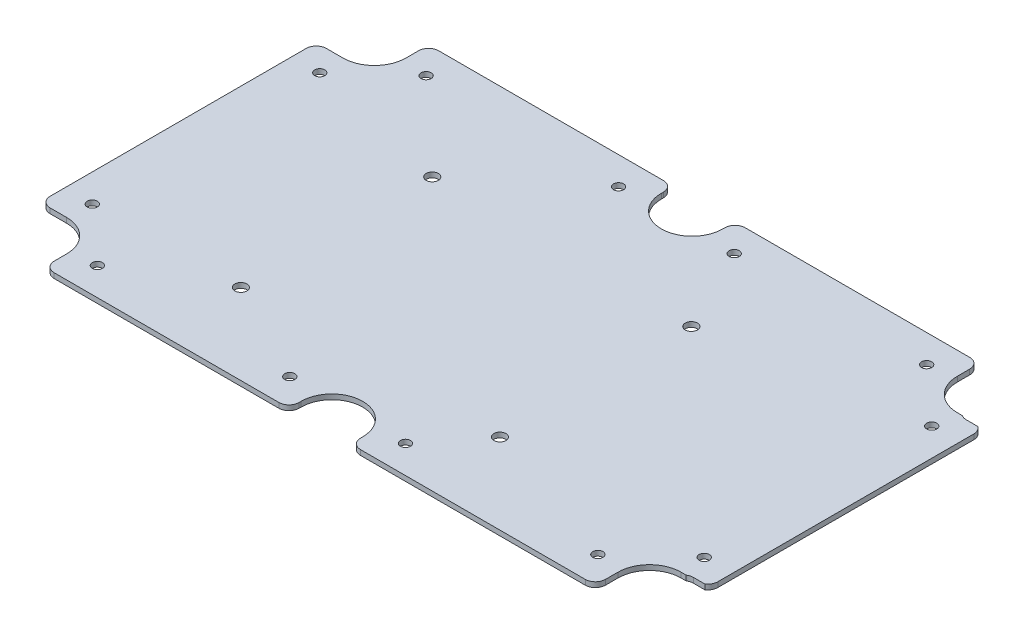
SolidWorks part; units mm, degrees
ref_plane "Front Plane" through (0, 0, 0) normal (0, 0, 1) x (1, 0, 0)
ref_plane "Top Plane" through (0, 0, 0) normal (0, 1, 0) x (1, 0, 0)
ref_plane "Right Plane" through (0, 0, 0) normal (1, 0, 0) x (0, 0, -1)
ref_plane "Plane1" through (0, 9.652, 0) normal (0, -1, 0) x (1, 0, 0)
sketch "Sketch1" plane through (0, 9.652, 0) normal (0, -1, 0) x (1, 0, 0)
  line L0 (-9.6495, -57.089) -> (-9.6495, -56.4515)
  line L1 (9.6495, -56.4515) -> (9.6495, -57.089)
  line L2 (12.8245, -60.264) -> (83.2283, -60.264)
  line L3 (86.4033, -57.089) -> (86.4033, -53.1978)
  line L4 (96.3068, -43.2943) -> (97.9048, -43.2943)
  line L5 (99.642, -42.7769) -> (103.2127, -42.7769)
  line L6 (104.6505, -40.1193) -> (104.6505, 40.1193)
  line L7 (103.2127, 42.7769) -> (99.642, 42.7769)
  line L8 (97.9048, 43.2943) -> (96.3068, 43.2943)
  line L9 (86.4033, 53.1978) -> (86.4033, 57.089)
  line L10 (83.2283, 60.264) -> (12.8245, 60.264)
  line L11 (9.6495, 57.089) -> (9.6495, 56.4515)
  line L12 (-9.6495, 56.4515) -> (-9.6495, 57.089)
  line L13 (-12.8245, 60.264) -> (-83.2283, 60.264)
  line L14 (-86.4033, 57.089) -> (-86.4033, 53.1978)
  line L15 (-96.3068, 43.2943) -> (-101.4755, 43.2943)
  line L16 (-104.6505, 40.1193) -> (-104.6505, -40.1193)
  line L17 (-101.4755, -43.2943) -> (-96.3068, -43.2943)
  line L18 (-86.4033, -53.1978) -> (-86.4033, -57.089)
  line L19 (-83.2283, -60.264) -> (-12.8245, -60.264)
  circle A0 centre (18.1292, 51.5303) radius 1.5875
  circle A1 centre (18.1292, -51.5303) radius 1.5875
  circle A2 centre (95.9167, -35.6553) radius 1.5875
  circle A3 centre (78.4543, 51.5303) radius 1.5875
  circle A4 centre (-95.9167, 35.6553) radius 1.5875
  circle A5 centre (-78.4543, -51.5303) radius 1.5875
  circle A6 centre (-18.1292, -51.5303) radius 1.5875
  circle A7 centre (-95.9167, -35.6553) radius 1.5875
  circle A8 centre (-78.4543, 51.5303) radius 1.5875
  circle A9 centre (95.9167, 35.6553) radius 1.5875
  circle A10 centre (78.4543, -51.5303) radius 1.5875
  circle A11 centre (-18.1292, 51.5303) radius 1.5875
  arc A12 (-12.8245, -60.264) -> (-9.6495, -57.089) centre (-12.8245, -57.089) ccw
  arc A13 (-9.6495, -56.4515) -> (9.6495, -56.4515) centre (0, -56.4515) cw
  arc A14 (9.6495, -57.089) -> (12.8245, -60.264) centre (12.8245, -57.089) ccw
  arc A15 (83.2283, -60.264) -> (86.4033, -57.089) centre (83.2283, -57.089) ccw
  arc A16 (86.4033, -53.1978) -> (96.3068, -43.2943) centre (96.3068, -53.1978) cw
  arc A17 (97.9048, -43.2943) -> (99.642, -42.7769) centre (99.642, -45.9519) cw
  arc A18 (103.2127, -42.7769) -> (104.6505, -40.1193) centre (101.4755, -40.1193) ccw
  arc A19 (104.6505, 40.1193) -> (103.2127, 42.7769) centre (101.4755, 40.1193) ccw
  arc A20 (99.642, 42.7769) -> (97.9048, 43.2943) centre (99.642, 45.9519) cw
  arc A21 (96.3068, 43.2943) -> (86.4033, 53.1978) centre (96.3068, 53.1978) cw
  arc A22 (86.4033, 57.089) -> (83.2283, 60.264) centre (83.2283, 57.089) ccw
  arc A23 (12.8245, 60.264) -> (9.6495, 57.089) centre (12.8245, 57.089) ccw
  arc A24 (9.6495, 56.4515) -> (-9.6495, 56.4515) centre (0, 56.4515) cw
  arc A25 (-9.6495, 57.089) -> (-12.8245, 60.264) centre (-12.8245, 57.089) ccw
  arc A26 (-83.2283, 60.264) -> (-86.4033, 57.089) centre (-83.2283, 57.089) ccw
  arc A27 (-86.4033, 53.1978) -> (-96.3068, 43.2943) centre (-96.3068, 53.1978) cw
  arc A28 (-101.4755, 43.2943) -> (-104.6505, 40.1193) centre (-101.4755, 40.1193) ccw
  arc A29 (-104.6505, -40.1193) -> (-101.4755, -43.2943) centre (-101.4755, -40.1193) ccw
  arc A30 (-96.3068, -43.2943) -> (-86.4033, -53.1978) centre (-96.3068, -53.1978) cw
  arc A31 (-86.4033, -57.089) -> (-83.2283, -60.264) centre (-83.2283, -57.089) ccw
extrude "Boss-Extrude1" add sketch "Sketch1" against normal blind 1.5875
sketch "Sketch2" plane through (0, 11.2395, 0) normal (0, 1, 0) x (1, 0, 0)
  line L1 (-50, -35) -> (-50, 25)
  line L2 (-50, 25) -> (31.21, 25)
  line L3 (31.21, 25) -> (31.21, -35)
  line L4 (31.21, -35) -> (-50, -35)
  circle A0 centre (-50, 25) radius 1.9
  circle A1 centre (-50, -35) radius 1.9
  circle A2 centre (31.21, -35) radius 1.9
  circle A3 centre (31.21, 25) radius 1.9
  point P6 (-50, -5)
  dimension "D4" = 3.8
  dimension "D5" = 3.8
  dimension "D6" = 3.8
  dimension "D7" = 3.8
  dimension "D1" = 50
  dimension "D2" = 60
  dimension "D3" = 81.21
  dimension "D8" = 25
extrude "Cut-Extrude1" cut sketch "Sketch2" against normal blind 10 contours L2 A0 L1 | L1 A0 L2 | L1 A1 L4 | L4 A1 L1 | L4 A2 L3 | L3 A2 L4 | L3 A3 L2 | L2 A3 L3
